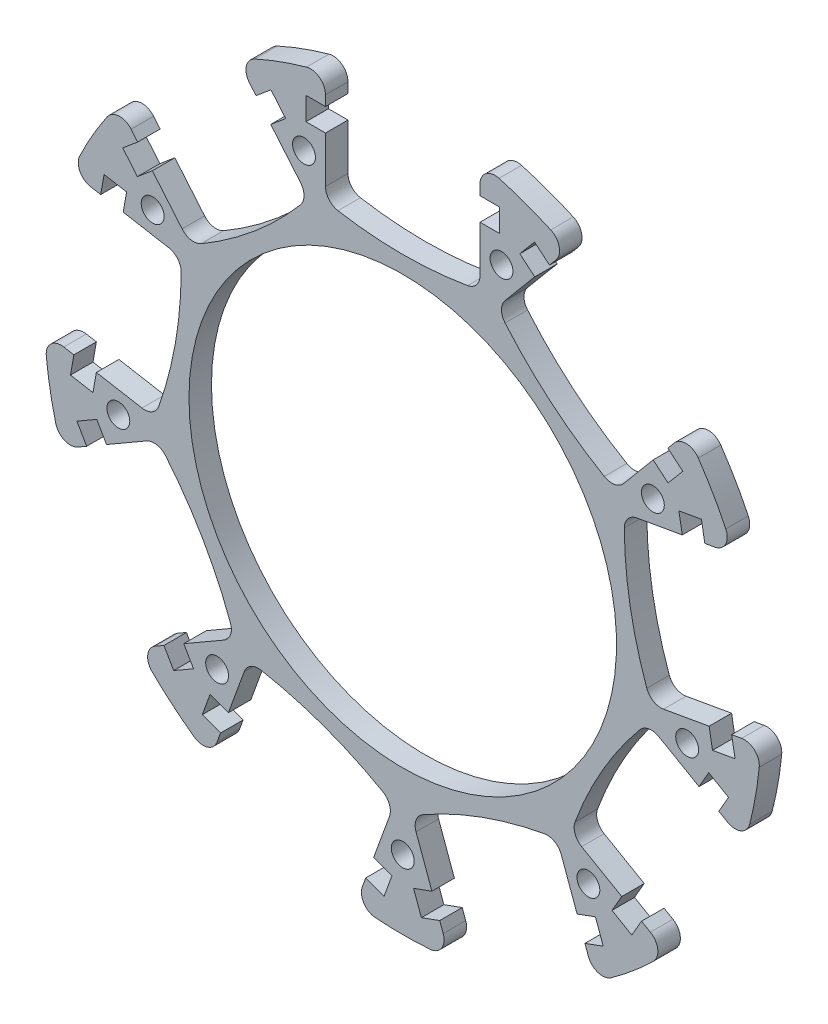
SolidWorks part; units mm, degrees
material "ﾎﾟﾘｶｰﾎﾞﾈｰﾄ(PC)高粘度"
ref_plane "正面" through (0, 0, 0) normal (0, 0, 1) x (1, 0, 0)
ref_plane "平面" through (0, 0, 0) normal (0, 1, 0) x (1, 0, 0)
ref_plane "右側面" through (0, 0, 0) normal (1, 0, 0) x (0, 0, -1)
sketch "ｽｹｯﾁ1" plane through (0, 0, 0) normal (0, 0, 1) x (1, 0, 0)
  circle A0 centre (0, 0) radius 47.75
  dimension "D1" = 95.5
extrude "ﾎﾞｽ - 押し出し1" add sketch "ｽｹｯﾁ1" along normal blind 3
sketch "ｽｹｯﾁ2" plane through (0, 0, 3) normal (0, 0, 1) x (1, 0, 0)
  line L0 (-10.3, 46.6259) -> (-10.3, 42.705)
  line L1 (10.3, 46.6259) -> (10.3, 42.705)
  line L2 (0, 47.75) -> (0, -47.75) construction
  line L3 (-10.3, 39.655) -> (-10.3, 31.8257)
  line L4 (12.9, 39.655) -> (10.3, 39.655)
  line L5 (12.9, 39.655) -> (12.9, 42.705)
  line L6 (12.9, 42.705) -> (10.3, 42.705)
  line L7 (-12.9, 39.655) -> (-12.9, 42.705)
  line L8 (12.9, 39.655) -> (-12.9, 42.705) construction
  line L9 (12.9, 42.705) -> (-12.9, 39.655) construction
  line L10 (-10.3, 39.655) -> (-12.9, 39.655)
  line L11 (-10.3, 42.705) -> (-12.9, 42.705)
  line L12 (10.3, 39.655) -> (10.3, 31.8257)
  line L13 (0, 30.78) -> (0, 41.18) construction
  line L14 (17.5995, 36.9982) -> (12.5669, 31.0006)
  line L15 (17.5995, 36.9982) -> (15.6078, 38.6695)
  line L16 (15.6078, 38.6695) -> (17.5683, 41.0059)
  line L17 (19.56, 39.3346) -> (17.5683, 41.0059)
  line L18 (22.0803, 42.3382) -> (19.56, 39.3346)
  line L19 (37.8608, 29.0968) -> (35.3405, 26.0932)
  line L20 (37.3322, 24.422) -> (35.3405, 26.0932)
  line L21 (35.3717, 22.0855) -> (37.3322, 24.422)
  line L22 (35.3717, 22.0855) -> (33.38, 23.7568)
  line L23 (33.38, 23.7568) -> (28.3474, 17.7592)
  line L24 (37.264, 17.0295) -> (29.5536, 15.67)
  line L25 (37.264, 17.0295) -> (36.8125, 19.59)
  line L26 (36.8125, 19.59) -> (39.8162, 20.1197)
  line L27 (40.2676, 17.5592) -> (39.8162, 20.1197)
  line L28 (44.1289, 18.24) -> (40.2676, 17.5592)
  line L29 (47.7061, -2.047) -> (43.8448, -2.7279)
  line L30 (44.2963, -5.2884) -> (43.8448, -2.7279)
  line L31 (41.2926, -5.818) -> (44.2963, -5.2884)
  line L32 (41.2926, -5.818) -> (40.8411, -3.2575)
  line L33 (40.8411, -3.2575) -> (33.1308, -4.617)
  line L34 (39.4922, -10.9074) -> (32.7119, -6.9928)
  line L35 (39.4922, -10.9074) -> (40.7922, -8.6558)
  line L36 (40.7922, -8.6558) -> (43.4336, -10.1808)
  line L37 (42.1336, -12.4324) -> (43.4336, -10.1808)
  line L38 (45.5292, -14.3929) -> (42.1336, -12.4324)
  line L39 (35.2292, -32.233) -> (31.8336, -30.2726)
  line L40 (30.5336, -32.5242) -> (31.8336, -30.2726)
  line L41 (27.8922, -30.9992) -> (30.5336, -32.5242)
  line L42 (27.8922, -30.9992) -> (29.1922, -28.7476)
  line L43 (29.1922, -28.7476) -> (22.4119, -24.8329)
  line L44 (23.2416, -33.7407) -> (20.5639, -26.3836)
  line L45 (23.2416, -33.7407) -> (25.6848, -32.8515)
  line L46 (25.6848, -32.8515) -> (26.728, -35.7175)
  line L47 (24.2848, -36.6068) -> (26.728, -35.7175)
  line L48 (25.6258, -40.2912) -> (24.2848, -36.6068)
  line L49 (6.2682, -47.3368) -> (4.9271, -43.6524)
  line L50 (2.4839, -44.5416) -> (4.9271, -43.6524)
  line L51 (1.4408, -41.6756) -> (2.4839, -44.5416)
  line L52 (1.4408, -41.6756) -> (3.884, -40.7863)
  line L53 (3.884, -40.7863) -> (1.2062, -33.4292)
  line L54 (-3.884, -40.7863) -> (-1.2062, -33.4292)
  line L55 (-3.884, -40.7863) -> (-1.4408, -41.6756)
  line L56 (-1.4408, -41.6756) -> (-2.4839, -44.5416)
  line L57 (-4.9271, -43.6524) -> (-2.4839, -44.5416)
  line L58 (-6.2682, -47.3368) -> (-4.9271, -43.6524)
  line L59 (-25.6258, -40.2912) -> (-24.2848, -36.6068)
  line L60 (-26.728, -35.7175) -> (-24.2848, -36.6068)
  line L61 (-25.6848, -32.8515) -> (-26.728, -35.7175)
  line L62 (-25.6848, -32.8515) -> (-23.2416, -33.7407)
  line L63 (-23.2416, -33.7407) -> (-20.5639, -26.3836)
  line L64 (-29.1922, -28.7476) -> (-22.4119, -24.8329)
  line L65 (-29.1922, -28.7476) -> (-27.8922, -30.9992)
  line L66 (-27.8922, -30.9992) -> (-30.5336, -32.5242)
  line L67 (-31.8336, -30.2726) -> (-30.5336, -32.5242)
  line L68 (-35.2292, -32.233) -> (-31.8336, -30.2726)
  line L69 (-45.5292, -14.3929) -> (-42.1336, -12.4324)
  line L70 (-43.4336, -10.1808) -> (-42.1336, -12.4324)
  line L71 (-40.7922, -8.6558) -> (-43.4336, -10.1808)
  line L72 (-40.7922, -8.6558) -> (-39.4922, -10.9074)
  line L73 (-39.4922, -10.9074) -> (-32.7119, -6.9928)
  line L74 (-40.8411, -3.2575) -> (-33.1308, -4.617)
  line L75 (-40.8411, -3.2575) -> (-41.2926, -5.818)
  line L76 (-41.2926, -5.818) -> (-44.2963, -5.2884)
  line L77 (-43.8448, -2.7279) -> (-44.2963, -5.2884)
  line L78 (-47.7061, -2.047) -> (-43.8448, -2.7279)
  line L79 (-44.1289, 18.24) -> (-40.2676, 17.5592)
  line L80 (-39.8162, 20.1197) -> (-40.2676, 17.5592)
  line L81 (-36.8125, 19.59) -> (-39.8162, 20.1197)
  line L82 (-36.8125, 19.59) -> (-37.264, 17.0295)
  line L83 (-37.264, 17.0295) -> (-29.5536, 15.67)
  line L84 (-33.38, 23.7568) -> (-28.3474, 17.7592)
  line L85 (-33.38, 23.7568) -> (-35.3717, 22.0855)
  line L86 (-35.3717, 22.0855) -> (-37.3322, 24.422)
  line L87 (-35.3405, 26.0932) -> (-37.3322, 24.422)
  line L88 (-37.8608, 29.0968) -> (-35.3405, 26.0932)
  line L89 (-22.0803, 42.3382) -> (-19.56, 39.3346)
  line L90 (-17.5683, 41.0059) -> (-19.56, 39.3346)
  line L91 (-15.6078, 38.6695) -> (-17.5683, 41.0059)
  line L92 (-15.6078, 38.6695) -> (-17.5995, 36.9982)
  line L93 (-17.5995, 36.9982) -> (-12.5669, 31.0006)
  circle A0 centre (0, 0) radius 47.75 construction
  arc A1 (-10.3, 46.6259) -> (10.3, 46.6259) centre (0, 0) cw
  arc A2 (-10.3, 31.8257) -> (10.3, 31.8257) centre (0, 82.03) ccw
  arc A3 (12.5669, 31.0006) -> (28.3474, 17.7592) centre (52.7279, 62.8386) ccw
  arc A4 (22.0803, 42.3382) -> (37.8608, 29.0968) centre (0, 0) cw
  arc A5 (29.5536, 15.67) -> (33.1308, -4.617) centre (80.7838, 14.2444) ccw
  arc A6 (44.1289, 18.24) -> (47.7061, -2.047) centre (0, 0) cw
  arc A7 (32.7119, -6.9928) -> (22.4119, -24.8329) centre (71.0401, -41.015) ccw
  arc A8 (45.5292, -14.3929) -> (35.2292, -32.233) centre (0, 0) cw
  arc A9 (20.5639, -26.3836) -> (1.2062, -33.4292) centre (28.0559, -77.083) ccw
  arc A10 (25.6258, -40.2912) -> (6.2682, -47.3368) centre (0, 0) cw
  arc A11 (-1.2062, -33.4292) -> (-20.5639, -26.3836) centre (-28.0559, -77.083) ccw
  arc A12 (-6.2682, -47.3368) -> (-25.6258, -40.2912) centre (0, 0) cw
  arc A13 (-22.4119, -24.8329) -> (-32.7119, -6.9928) centre (-71.0401, -41.015) ccw
  arc A14 (-35.2292, -32.233) -> (-45.5292, -14.3929) centre (0, 0) cw
  arc A15 (-33.1308, -4.617) -> (-29.5536, 15.67) centre (-80.7838, 14.2444) ccw
  arc A16 (-47.7061, -2.047) -> (-44.1289, 18.24) centre (0, 0) cw
  arc A17 (-28.3474, 17.7592) -> (-12.5669, 31.0006) centre (-52.7279, 62.8386) ccw
  arc A18 (-37.8608, 29.0968) -> (-22.0803, 42.3382) centre (0, 0) cw
  point P11 (0, 41.18)
  point P139 (0, 0)
  dimension "D2" = 20.6
  dimension "D7" = 51.25
  dimension "D1" = 41.18
  dimension "D3" = 10.3
  dimension "D4" = 3.05
  dimension "D5" = 25.8
  dimension "D6" = 10.4
  dimension "D8" = 9
extrude "ｶｯﾄ - 押し出し1" cut sketch "ｽｹｯﾁ2" against normal through all
fillet "ﾌｨﾚｯﾄ2" radius 2 36 edges at (-12.5669, 31.0006, 1.5) (-28.3474, 17.7592, 1.5) (-29.5536, 15.67, 1.5) (-33.1308, -4.617, 1.5) (-32.7119, -6.9928, 1.5) (-22.4119, -24.8329, 1.5) (-20.5639, -26.3836, 1.5) (-1.2062, -33.4292, 1.5) (1.2062, -33.4292, 1.5) (20.5639, -26.3836, 1.5) (32.7119, -6.9928, 1.5) (22.4119, -24.8329, 1.5) (33.1308, -4.617, 1.5) (29.5536, 15.67, 1.5) (28.3474, 17.7592, 1.5) (12.5669, 31.0006, 1.5) (10.3, 31.8257, 1.5) (-10.3, 31.8257, 1.5) (35.2292, -32.233, 1.5) (25.6258, -40.2912, 1.5) (6.2682, -47.3368, 1.5) (-6.2682, -47.3368, 1.5) (-25.6258, -40.2912, 1.5) (-35.2292, -32.233, 1.5) (-45.5292, -14.3929, 1.5) (-47.7061, -2.047, 1.5) (-44.1289, 18.24, 1.5) (-37.8608, 29.0968, 1.5) (-22.0803, 42.3382, 1.5) (-10.3, 46.6259, 1.5) (22.0803, 42.3382, 1.5) (10.3, 46.6259, 1.5) (37.8608, 29.0968, 1.5) (44.1289, 18.24, 1.5) (47.7061, -2.047, 1.5) (45.5292, -14.3929, 1.5)
sketch "ｽｹｯﾁ3" plane through (0, 0, 3) normal (0, 0, 1) x (1, 0, 0)
  line L0 (0, 0) -> (0, -38.5) construction
  line L1 (0, 0) -> (-24.7473, -29.4927) construction
  line L2 (0, 0) -> (-37.9151, -6.6855) construction
  line L3 (0, 0) -> (-33.342, 19.25) construction
  line L4 (0, 0) -> (-13.1678, 36.1782) construction
  line L5 (0, 0) -> (13.1678, 36.1782) construction
  line L6 (0, 0) -> (33.342, 19.25) construction
  line L7 (0, 0) -> (37.9151, -6.6855) construction
  line L8 (0, 0) -> (24.7473, -29.4927) construction
  circle A2 centre (0, -38.5) radius 1.525
  circle A3 centre (0, 0) radius 38.5 construction
  circle A4 centre (-24.7473, -29.4927) radius 1.525
  circle A5 centre (0, 0) radius 38.5 construction
  circle A6 centre (-37.9151, -6.6855) radius 1.525
  circle A7 centre (0, 0) radius 38.5 construction
  circle A8 centre (-33.342, 19.25) radius 1.525
  circle A9 centre (0, 0) radius 38.5 construction
  circle A10 centre (-13.1678, 36.1782) radius 1.525
  circle A11 centre (0, 0) radius 38.5 construction
  circle A12 centre (13.1678, 36.1782) radius 1.525
  circle A13 centre (0, 0) radius 38.5 construction
  circle A14 centre (33.342, 19.25) radius 1.525
  circle A15 centre (0, 0) radius 38.5 construction
  circle A16 centre (37.9151, -6.6855) radius 1.525
  circle A17 centre (0, 0) radius 38.5 construction
  circle A18 centre (24.7473, -29.4927) radius 1.525
  circle A19 centre (0, 0) radius 38.5 construction
  point P10 (0, 0)
  point P32 (0, 0)
  dimension "D1" = 3.05
  dimension "D2" = 77
  dimension "D3" = 9
extrude "ｶｯﾄ - 押し出し2" cut sketch "ｽｹｯﾁ3" against normal through all
sketch "ｽｹｯﾁ6" plane through (0, 0, 0) normal (0, 0, -1) x (-1, 0, 0)
  circle A19 centre (0, 0) radius 28.5
  dimension "D1" = 57
extrude "ｶｯﾄ - 押し出し4" cut sketch "ｽｹｯﾁ6" against normal through all
